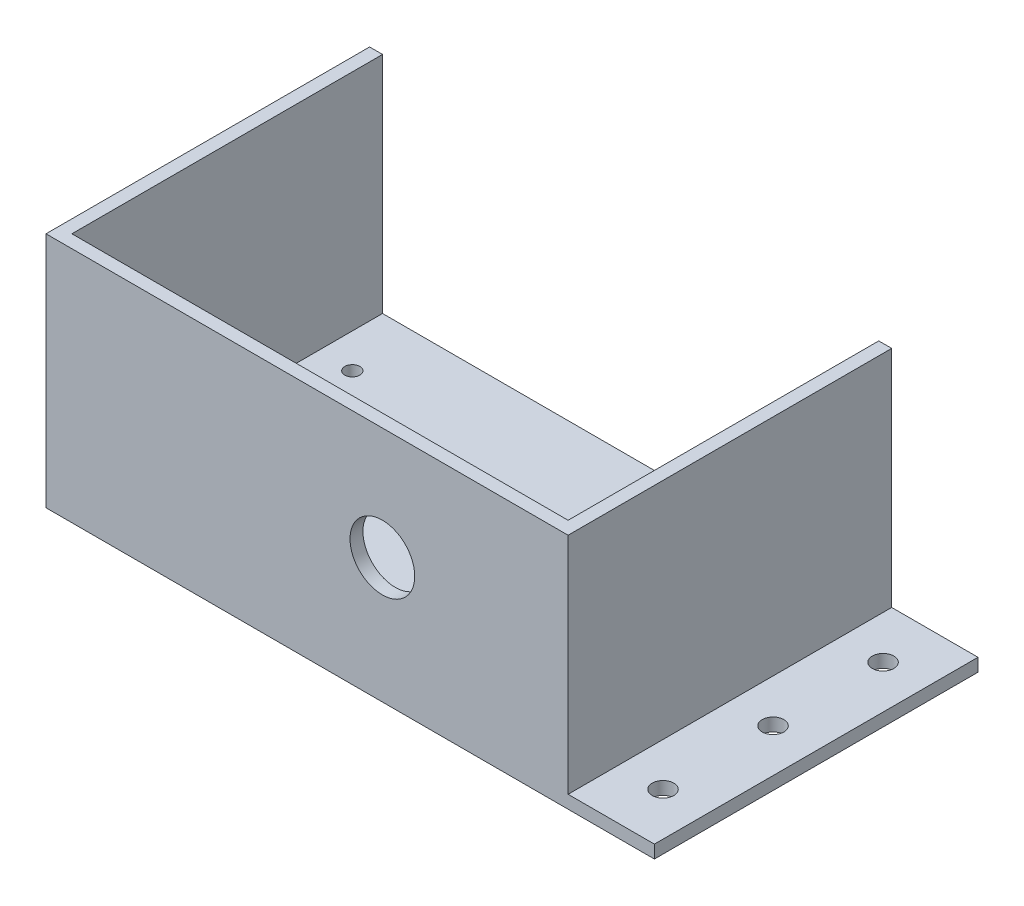
SolidWorks part; units mm, degrees
ref_plane "Front Plane" through (0, 0, 0) normal (0, 0, 1) x (1, 0, 0)
ref_plane "Top Plane" through (0, 0, 0) normal (0, 1, 0) x (1, 0, 0)
ref_plane "Right Plane" through (0, 0, 0) normal (1, 0, 0) x (0, 0, -1)
sketch "Sketch1" plane through (0, 0, 0) normal (0, 1, 0) x (1, 0, 0)
  line L1 (0, 0) -> (121, 0)
  line L2 (0, 0) -> (0, 75)
  line L3 (0, 75) -> (121, 75)
  line L4 (121, 0) -> (121, 75)
  dimension "D1" = 121
  dimension "D2" = 75
extrude "Boss-Extrude1" add sketch "Sketch1" along normal blind 58
sketch "Sketch2" plane through (0, 0, -75) normal (0, 0, -1) x (-1, 0, 0)
  line L0 (-121, 0) -> (0, 0) construction
  line L1 (-3, 3) -> (-118, 3)
  line L2 (-3, 3) -> (-3, 56)
  line L3 (-3, 56) -> (-118, 56)
  line L4 (-118, 3) -> (-118, 56)
  line L5 (0, 58) -> (0, 0) construction
  line L6 (-121, 58) -> (-121, 0) construction
  dimension "D1" = 53
  dimension "D2" = 3
  dimension "D3" = 3
  dimension "D4" = 3
extrude "Cut-Extrude1" cut sketch "Sketch2" against normal blind 72
sketch "Sketch4" plane through (0, 58, 0) normal (0, 1, 0) x (1, 0, 0)
  text T0 "IMAGINEER" font "Century Gothic" height 10
extrude "Boss-Extrude2" add sketch "Sketch4" along normal blind 1.5
sketch "Sketch5" plane through (0, 58, 0) normal (0, 1, 0) x (-1, 0, 0)
  line L12 (-60.5, 72.992) -> (-60.5, -137.1284) construction
  line L13 (-84.629, -12.2531) -> (-42.629, -12.2531)
  line L14 (-42.629, -12.2531) -> (-36.329, -18.1531)
  line L15 (-36.329, -18.1531) -> (-36.329, -34.1531)
  line L16 (-36.329, -34.1531) -> (-42.629, -40.0531)
  line L17 (-84.629, -12.2531) -> (-84.629, -40.0531)
  line L18 (-84.629, -40.0531) -> (-42.629, -40.0531)
  circle A4 centre (-60.4781, -46.043) radius 1.4898
  circle A5 centre (-60.5065, -6.2504) radius 1.5
  dimension "D1" = 60.5
extrude "Cut-Extrude2" cut sketch "Sketch5" against normal blind 5
sketch "Sketch6" plane through (121, 0, 0) normal (1, 0, 0) x (0, 0, -1)
  line L0 (75, 58) -> (75, 0) construction
  line L1 (0, 0) -> (75, 0)
  line L2 (0, 0) -> (0, 3)
  line L3 (0, 3) -> (75, 3)
  line L4 (75, 0) -> (75, 3)
  dimension "D1" = 3
extrude "Boss-Extrude3" add sketch "Sketch6" along normal blind 20
sketch "Sketch7" plane through (0, 3, 0) normal (0, 1, 0) x (1, 0, 0)
  line L0 (141, 75) -> (141, 0) construction
  line L1 (141, 75) -> (121, 75) construction
  line L2 (141, 0) -> (121, 0) construction
  circle A0 centre (131, 63) radius 2.5
  circle A1 centre (131, 37.5) radius 2.5
  circle A2 centre (131, 12) radius 2.5
  dimension "D1" = 5
  dimension "D2" = 10
  dimension "D3" = 12
  dimension "D4" = 12
  dimension "D5" = 25.5
extrude "Cut-Extrude3" cut sketch "Sketch7" against normal blind 20
sketch "Sketch8" plane through (0, 0, 0) normal (0, 0, 1) x (1, 0, 0)
  line L0 (0, 0) -> (141, 0) construction
  circle A1 centre (77.9556, 29) radius 7.5
  dimension "D1" = 29
extrude "Cut-Extrude4" cut sketch "Sketch8" against normal blind 5
sketch "Sketch9" plane through (0, 0, 0) normal (0, -1, 0) x (1, 0, 0)
  line L0 (141, -75) -> (0, -75) construction
  line L1 (0, -75) -> (0, 0) construction
  line L2 (141, 0) -> (141, -75) construction
  circle A0 centre (11, -60) radius 1.75
  circle A1 centre (110, -60) radius 1.75
  dimension "D1" = 3.5
  dimension "D2" = 15
  dimension "D3" = 11
  dimension "D4" = 31
extrude "Cut-Extrude5" cut sketch "Sketch9" against normal blind 5
sketch "Sketch10" plane through (0, 0, 0) normal (0, 0, 1) x (1, 0, 0)
  line L0 (0, 58) -> (0, 0) construction
  line L1 (0, 55) -> (121, 55)
  line L2 (0, 55) -> (0, 65.055)
  line L3 (0, 65.055) -> (121, 65.055)
  line L4 (121, 55) -> (121, 65.055)
  dimension "D1" = 3
extrude "Cut-Extrude6" cut sketch "Sketch10" against normal through all
